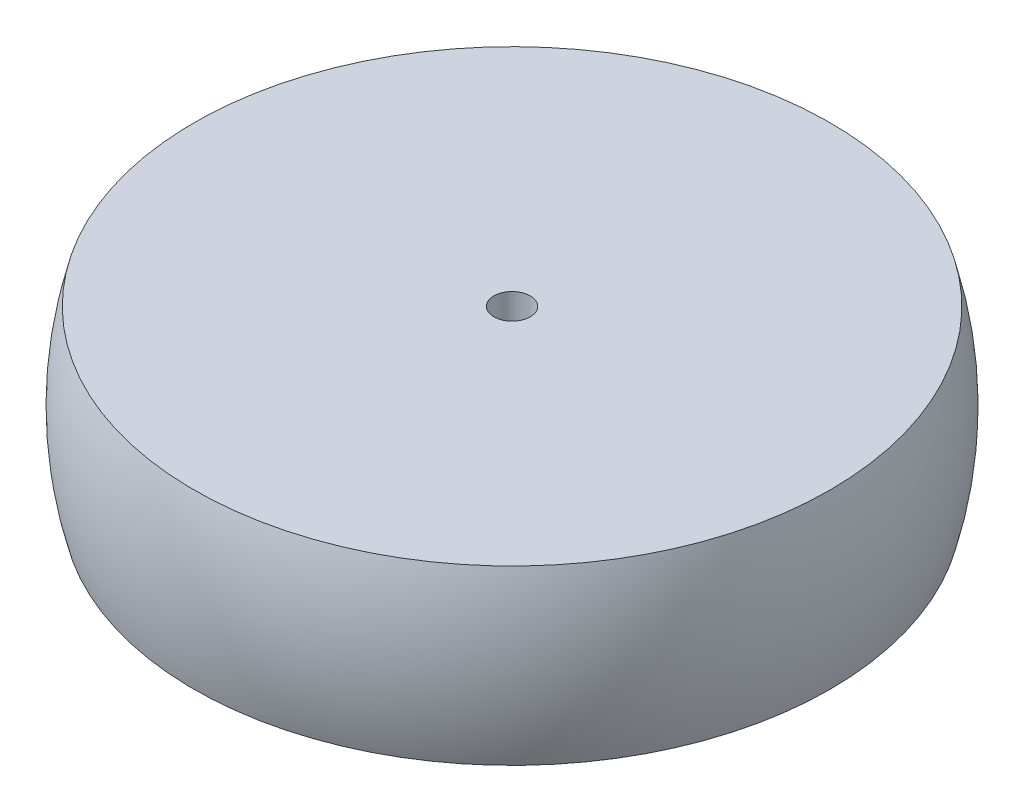
SolidWorks part; units mm, degrees
ref_plane "Front" through (0, 0, 0) normal (0, 0, 1) x (1, 0, 0)
ref_plane "Top" through (0, 0, 0) normal (0, 1, 0) x (1, 0, 0)
ref_plane "Right" through (0, 0, 0) normal (1, 0, 0) x (0, 0, -1)
sketch "Sketch1" plane through (0, 0, 0) normal (0, 0, 1) x (1, 0, 0)
  line L0 (0, 0) -> (0, 25)
  line L1 (0, 25) -> (35, 25)
  line L2 (0, 0) -> (6, 0)
  line L3 (6, 0) -> (6, 6)
  line L4 (6, 6) -> (35, 6)
  arc A0 (35, 25) -> (35, 6) centre (0, 15.5) cw
  dimension "D1" = 25
  dimension "D2" = 35
  dimension "D3" = 6
  dimension "D4" = 6
  dimension "D5" = 9.5
revolve "Revolve2" add sketch "Sketch1" angle 360 about L0
sketch "Sketch2" plane through (0, 0, 0) normal (0, -1, 0) x (1, 0, 0)
  circle A0 centre (0, 0) radius 2
  dimension "D1" = 4
extrude "Cut-Extrude1" cut sketch "Sketch2" against normal through all
